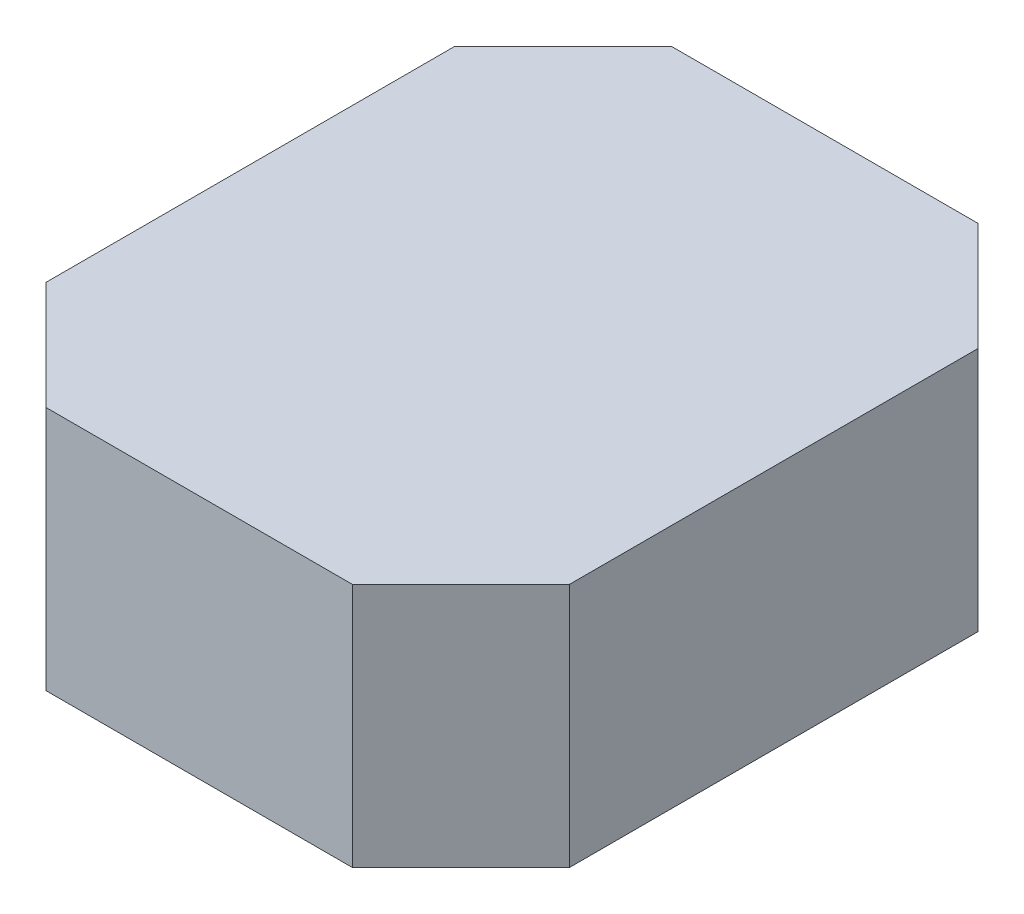
SolidWorks part; units mm, degrees
ref_plane "Front Plane" through (0, 0, 0) normal (0, 0, 1) x (1, 0, 0)
ref_plane "Top Plane" through (0, 0, 0) normal (0, 1, 0) x (1, 0, 0)
ref_plane "Right Plane" through (0, 0, 0) normal (1, 0, 0) x (0, 0, -1)
sketch "Sketch1" plane through (0, 0, 0) normal (0, 1, 0) x (1, 0, 0)
  line L0 (0, 657.9948) -> (0, -680.2163) construction
  line L1 (0, 0) -> (962.7742, 0) construction
  line L2 (962.7742, 0) -> (-1009.5154, 0) construction
  line L3 (-128.033, 100) -> (-128.033, -100)
  line L4 (-128.033, -100) -> (-75, -153.033)
  line L5 (-75, -153.033) -> (75, -153.033)
  line L6 (128.033, -100) -> (75, -153.033)
  line L7 (128.033, 100) -> (128.033, -100)
  line L8 (128.033, 100) -> (75, 153.033)
  line L9 (-75, 153.033) -> (75, 153.033)
  line L10 (-128.033, 100) -> (-75, 153.033)
  point P11 (0, -153.033)
  point P14 (128.033, 0)
  point P17 (-128.033, 0)
  dimension "D1" = 100
  dimension "D2" = 75
  dimension "D3" = 135
  dimension "D4" = 75
extrude "Boss-Extrude1" add sketch "Sketch1" along normal blind 120
